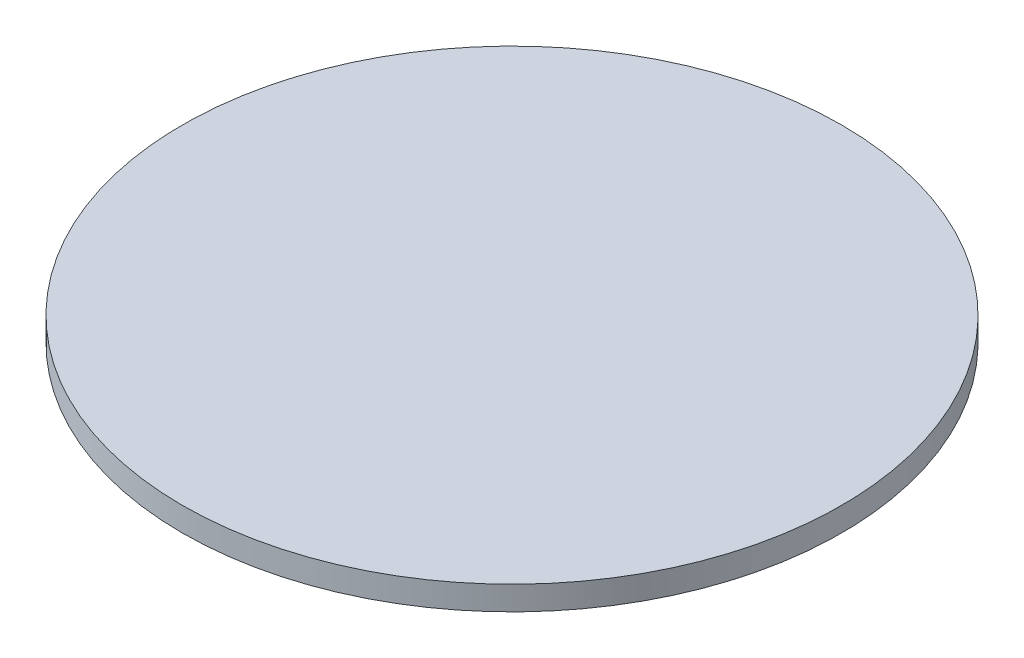
SolidWorks part; units mm, degrees
ref_plane "Front Plane" through (0, 0, 0) normal (0, 0, 1) x (1, 0, 0)
ref_plane "Top Plane" through (0, 0, 0) normal (0, 1, 0) x (1, 0, 0)
ref_plane "Right Plane" through (0, 0, 0) normal (1, 0, 0) x (0, 0, -1)
sketch "Sketch1" plane through (0, 0, 0) normal (0, 1, 0) x (1, 0, 0)
  circle A0 centre (0, 0) radius 165
  dimension "D1" = 330
extrude "Boss-Extrude1" add sketch "Sketch1" along normal blind 12
sketch "Sketch2" plane through (0, 0, 0) normal (0, -1, 0) x (1, 0, 0)
  circle A0 centre (0, 0) radius 145
  circle A1 centre (0, 0) radius 140
  dimension "D1" = 290
  dimension "D2" = 280
extrude "Cut-Extrude1" cut sketch "Sketch2" against normal blind 6
